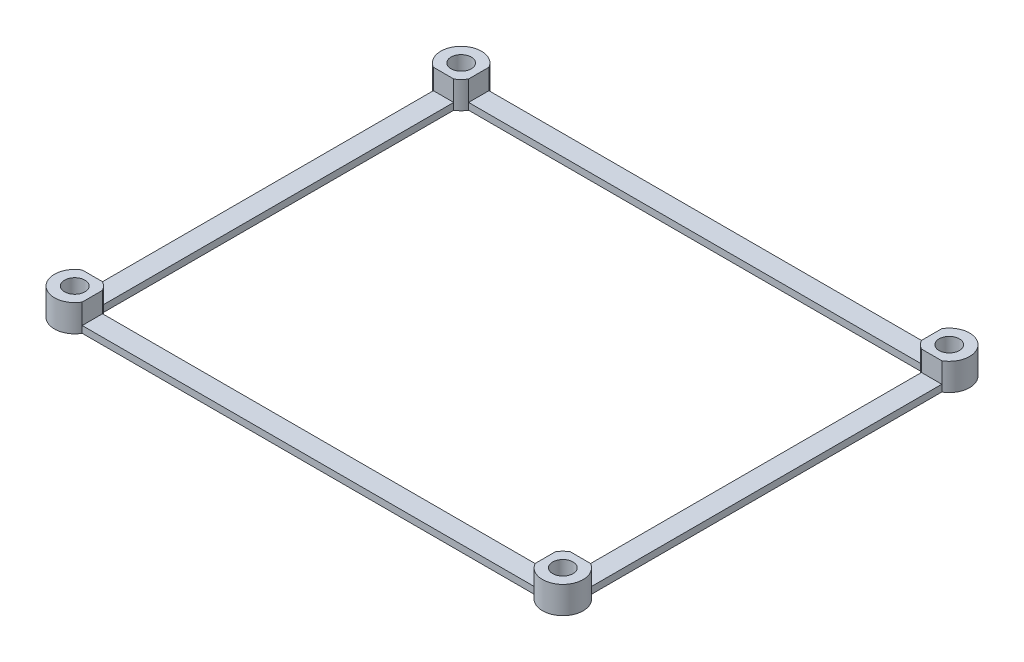
SolidWorks part; units mm, degrees
ref_plane "Front Plane" through (0, 0, 0) normal (0, 0, 1) x (1, 0, 0)
ref_plane "Top Plane" through (0, 0, 0) normal (0, 1, 0) x (1, 0, 0)
ref_plane "Right Plane" through (0, 0, 0) normal (1, 0, 0) x (0, 0, -1)
sketch "Sketch1" plane through (0, 0, 0) normal (0, 1, 0) x (1, 0, 0)
  line L1 (-36, -28.5) -> (36, -28.5) construction
  line L2 (-36, -28.5) -> (-36, 28.5) construction
  line L3 (-36, 28.5) -> (36, 28.5) construction
  line L4 (36, -28.5) -> (36, 28.5) construction
  line L5 (-36, -28.5) -> (36, 28.5) construction
  line L6 (-36, 28.5) -> (36, -28.5) construction
  line L7 (-33.4019, 27) -> (33.4019, 27)
  line L9 (-33.4019, 30) -> (33.4019, 30)
  line L11 (-33.4019, 27) -> (33.4019, 30) construction
  line L12 (-33.4019, 30) -> (33.4019, 27) construction
  line L14 (-37.5, -25.9019) -> (-37.5, 25.9019)
  line L16 (-34.5, -25.9019) -> (-34.5, 25.9019)
  line L17 (-37.5, -25.9019) -> (-34.5, 25.9019) construction
  line L18 (-37.5, 25.9019) -> (-34.5, -25.9019) construction
  line L20 (34.5, -25.9019) -> (34.5, 25.9019)
  line L22 (37.5, -25.9019) -> (37.5, 25.9019)
  line L23 (34.5, -25.9019) -> (37.5, 25.9019) construction
  line L24 (34.5, 25.9019) -> (37.5, -25.9019) construction
  line L25 (-33.4019, -30) -> (33.4019, -30)
  line L27 (-33.4019, -27) -> (33.4019, -27)
  line L29 (-33.4019, -30) -> (33.4019, -27) construction
  line L30 (-33.4019, -27) -> (33.4019, -30) construction
  circle A0 centre (36, 28.5) radius 1.5
  circle A1 centre (36, -28.5) radius 1.5
  circle A2 centre (-36, -28.5) radius 1.5
  circle A3 centre (-36, 28.5) radius 1.5
  arc A4 (-34.5, 25.9019) -> (-33.4019, 27) centre (-36, 28.5) ccw
  arc A5 (33.4019, 27) -> (34.5, 25.9019) centre (36, 28.5) ccw
  arc A6 (34.5, -25.9019) -> (33.4019, -27) centre (36, -28.5) ccw
  arc A7 (-33.4019, -27) -> (-34.5, -25.9019) centre (-36, -28.5) ccw
  arc A8 (-37.5, -25.9019) -> (-33.4019, -30) centre (-36, -28.5) ccw
  arc A9 (-33.4019, 30) -> (-37.5, 25.9019) centre (-36, 28.5) ccw
  arc A10 (37.5, 25.9019) -> (33.4019, 30) centre (36, 28.5) ccw
  arc A11 (33.4019, -30) -> (37.5, -25.9019) centre (36, -28.5) ccw
  point P0 (0, 0)
  point P14 (0, 28.5)
  point P19 (-36, 0)
  point P24 (36, 0)
  point P29 (0, -28.5)
  dimension "D3" = 3
  dimension "D4" = 6
  dimension "D1" = 72
  dimension "D2" = 57
  dimension "D5" = 3
  dimension "D6" = 3
  dimension "D7" = 3
  dimension "D8" = 3
extrude "Boss-Extrude1" add sketch "Sketch1" along normal blind 4
sketch "Sketch2" plane through (0, 4, 0) normal (0, 1, 0) x (1, 0, 0)
  line L1 (-37.5, 25.9019) -> (-34.5, 25.9019)
  line L2 (-37.5, 25.9019) -> (-37.5, -25.9019)
  line L3 (-37.5, -25.9019) -> (-34.5, -25.9019)
  line L4 (-34.5, 25.9019) -> (-34.5, -25.9019)
  line L5 (-33.4019, -27) -> (33.4019, -27)
  line L6 (-33.4019, -27) -> (-33.4019, -30)
  line L7 (-33.4019, -30) -> (33.4019, -30)
  line L8 (33.4019, -27) -> (33.4019, -30)
  line L9 (34.5, -25.9019) -> (37.5, -25.9019)
  line L10 (34.5, -25.9019) -> (34.5, 25.9019)
  line L11 (34.5, 25.9019) -> (37.5, 25.9019)
  line L12 (37.5, -25.9019) -> (37.5, 25.9019)
  line L13 (33.4019, 27) -> (-33.4019, 27)
  line L14 (33.4019, 27) -> (33.4019, 30)
  line L15 (33.4019, 30) -> (-33.4019, 30)
  line L16 (-33.4019, 27) -> (-33.4019, 30)
extrude "Cut-Extrude1" cut sketch "Sketch2" against normal offset from surface (3 mm away) 1 up to face at (-36, 0, -27)
